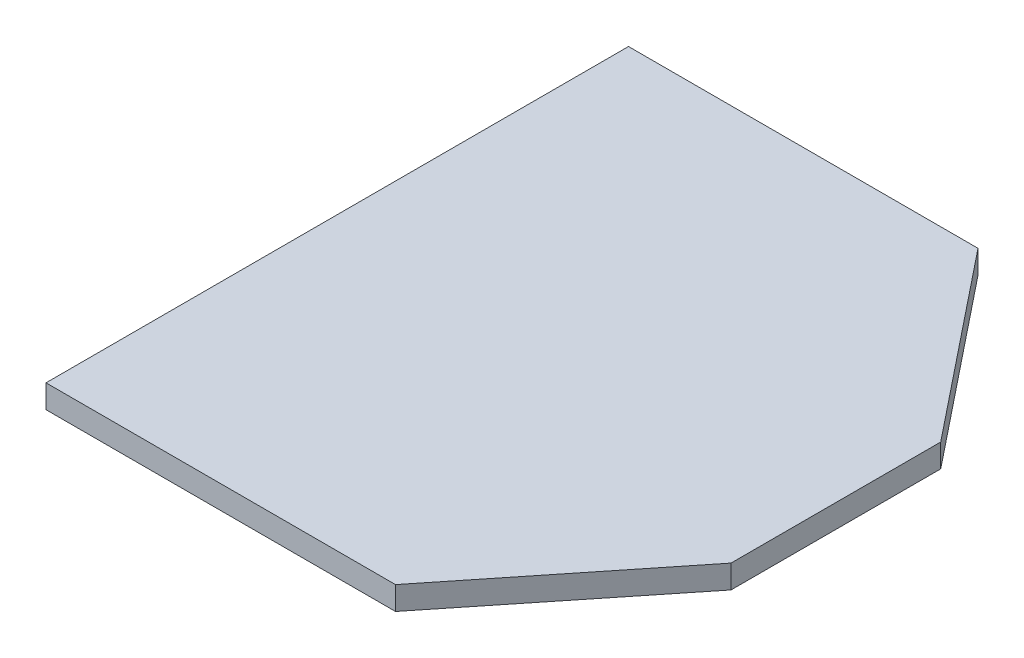
SolidWorks part; units mm, degrees
material "Nylon PA 12"
ref_plane "Front Plane" through (0, 0, 0) normal (0, 0, 1) x (1, 0, 0)
ref_plane "Top Plane" through (0, 0, 0) normal (0, 1, 0) x (1, 0, 0)
ref_plane "Right Plane" through (0, 0, 0) normal (1, 0, 0) x (0, 0, -1)
sketch "Sketch1" plane through (0, 0, 0) normal (0, 1, 0) x (1, 0, 0)
  line L0 (75, 125) -> (175, 0)
  line L1 (-75, -125) -> (75, -125)
  line L2 (-75, -125) -> (-75, 125)
  line L3 (-75, 125) -> (75, 125)
  line L5 (0, -55) -> (0, 55) construction
  line L7 (175, 0) -> (75, -125)
  point P0 (0, 0)
  dimension "D1" = 150
  dimension "D2" = 250
  dimension "D3" = 100
  dimension "D4" = 75
  dimension "D5" = 125
  dimension "D6" = 175
extrude "Boss-Extrude1" add sketch "Sketch1" along normal mid plane 10
sketch "Sketch2" [suppressed] plane through (0, 0, -125) normal (0, 0, -1) x (-1, 0, 0)
  line L0 (-75, -5) -> (75, -5)
  line L1 (75, -5) -> (75, -35)
  line L2 (75, -35) -> (-75, -35)
  line L3 (-75, -35) -> (-75, -5)
  dimension "D1" = 30
sketch "Sketch3" plane through (0, 5, 0) normal (0, 1, 0) x (1, 0, 0)
  line L5 (-5.5, 0) -> (5.5, 0) construction
  line L7 (175, 0) -> (175, 80.2527) construction
  line L8 (75, -125) -> (175, 0) construction
  line L9 (175, 0) -> (248.3172, 0) construction
  line L10 (175, 0) -> (75, 125) construction
  line L11 (175, 45) -> (139, 45)
  line L12 (175, 45) -> (175, -45)
  line L13 (175, -45) -> (139, -45)
  line L14 (139, 45) -> (139, -45)
  dimension "D1" = 45
  dimension "D2" = 45
  dimension "D3" = 36
extrude "Cut-Extrude1" cut sketch "Sketch3" against normal blind 10
